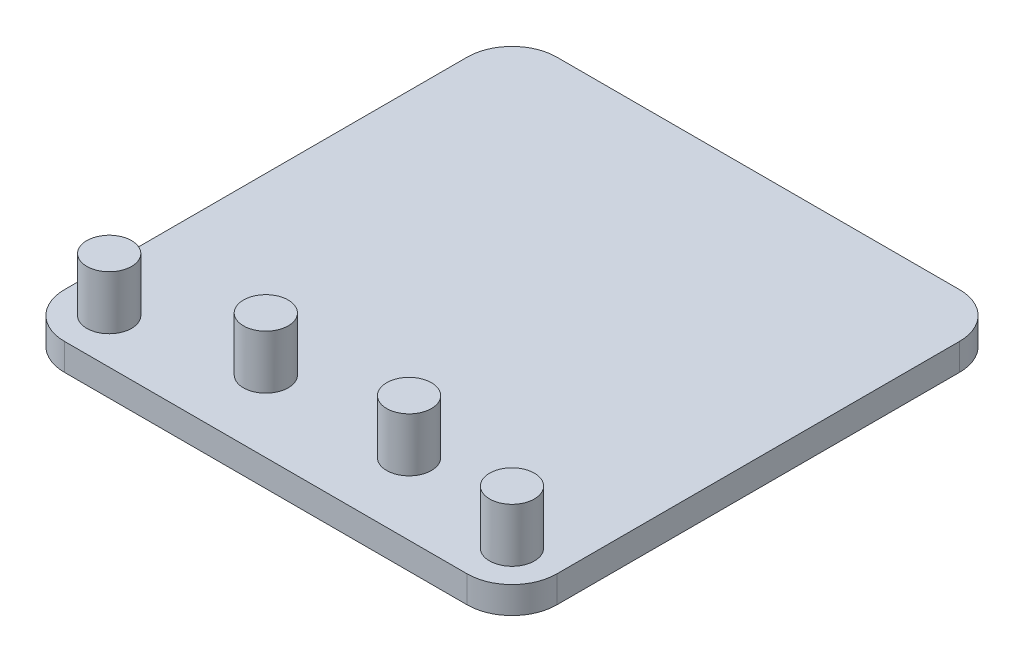
SolidWorks part; units mm, degrees
ref_plane "Front Plane" through (0, 0, 0) normal (0, 0, 1) x (1, 0, 0)
ref_plane "Top Plane" through (0, 0, 0) normal (0, 1, 0) x (1, 0, 0)
ref_plane "Right Plane" through (0, 0, 0) normal (1, 0, 0) x (0, 0, -1)
sketch "Sketch1" plane through (0, 0, 0) normal (0, 1, 0) x (1, 0, 0)
  line L1 (0, 0) -> (110, 0)
  line L2 (0, 0) -> (0, 110)
  line L3 (0, 110) -> (110, 110)
  line L4 (110, 0) -> (110, 110)
  dimension "D1" = 110
  dimension "D2" = 110
extrude "Boss-Extrude1" add sketch "Sketch1" along normal blind 6
fillet "Fillet1" radius 10 4 edges at (0, 3, -110) (110, 3, -110) (110, 3, 0) (0, 3, 0)
sketch "Sketch10" plane through (0, 6, 0) normal (0, 1, 0) x (1, 0, 0)
  line L0 (55, 110) -> (55, 0)
  line L1 (100, 110) -> (10, 110) construction
  line L2 (10, 0) -> (100, 0) construction
sketch "Sketch12" plane through (0, 6, 0) normal (0, 1, 0) x (1, 0, 0)
  line L0 (55, 110) -> (55, 0) construction
  line L1 (10, 0) -> (100, 0) construction
  circle A0 centre (39, 16) radius 5
  dimension "D1" = 16
  dimension "D2" = 16
extrude "Boss-Extrude5" add sketch "Sketch12" along normal blind 12
sketch "Sketch13" plane through (0, 6, 0) normal (0, 1, 0) x (1, 0, 0)
  line L0 (55, 110) -> (55, 0) construction
  line L1 (10, 0) -> (100, 0) construction
  circle A0 centre (71, 16) radius 5
  dimension "D1" = 16
  dimension "D2" = 16
extrude "Boss-Extrude6" add sketch "Sketch13" along normal blind 12
sketch "Sketch14" plane through (0, 6, 0) normal (0, 1, 0) x (1, 0, 0)
  line L0 (0, 100) -> (0, 10) construction
  line L1 (10, 0) -> (100, 0) construction
  circle A0 centre (10, 10) radius 5
  dimension "D1" = 10
  dimension "D2" = 10
extrude "Boss-Extrude7" add sketch "Sketch14" along normal blind 12
sketch "Sketch15" plane through (0, 6, 0) normal (0, 1, 0) x (1, 0, 0)
  circle A0 centre (100, 10) radius 5
  dimension "D1" = 10
  dimension "D2" = 10
extrude "Boss-Extrude8" add sketch "Sketch15" along normal blind 12
